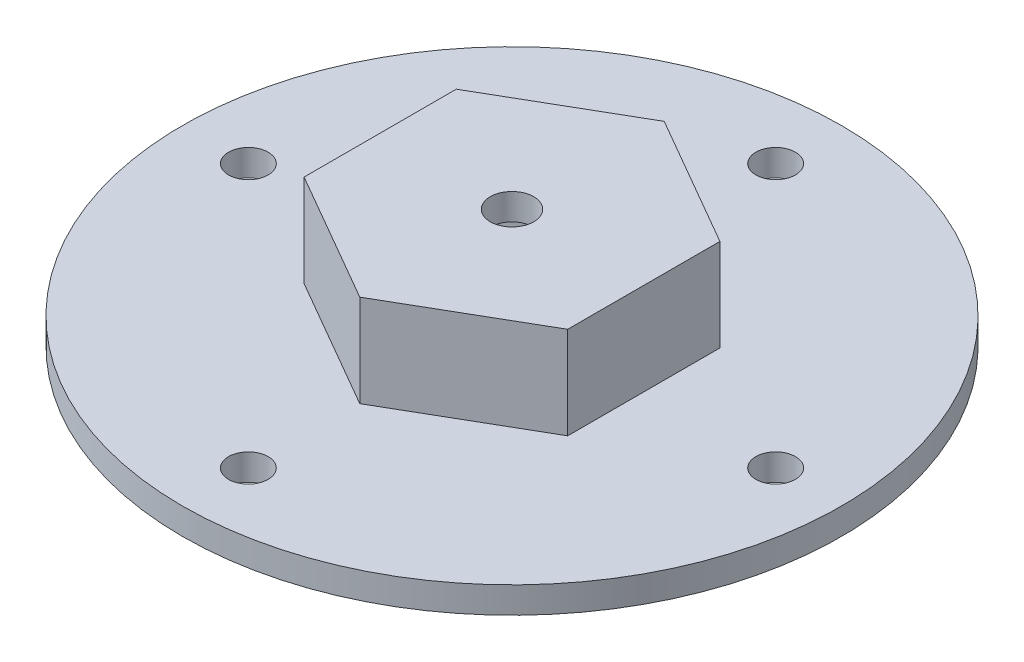
SolidWorks part; units mm, degrees
ref_plane "前视基准面" through (0, 0, 0) normal (0, 0, 1) x (1, 0, 0)
ref_plane "上视基准面" through (0, 0, 0) normal (0, 1, 0) x (1, 0, 0)
ref_plane "右视基准面" through (0, 0, 0) normal (1, 0, 0) x (0, 0, -1)
sketch "Sketch1" plane through (0, 0, 0) normal (0, 1, 0) x (1, 0, 0)
  circle A0 centre (0, 0) radius 25
  dimension "D1" = 50
extrude "Boss-Extrude1" add sketch "Sketch1" along normal blind 2
sketch "Sketch2" plane through (0, 2, 0) normal (0, 1, 0) x (1, 0, 0)
  circle A0 centre (0, 0) radius 20 construction
  circle A1 centre (0, 20) radius 1.5
  circle A2 centre (20, 0) radius 1.5
  circle A3 centre (0, -20) radius 1.5
  circle A4 centre (-20, 0) radius 1.5
  dimension "D1" = 4
extrude "Cut-Extrude1" cut sketch "Sketch2" against normal blind 3
sketch "Sketch3" plane through (0, 2, 0) normal (0, 1, 0) x (1, 0, 0)
  line L1 (0, 11.547) -> (-10, 5.7735)
  line L2 (-10, 5.7735) -> (-10, -5.7735)
  line L3 (-10, -5.7735) -> (0, -11.547)
  line L4 (0, -11.547) -> (10, -5.7735)
  line L5 (10, -5.7735) -> (10, 5.7735)
  line L6 (10, 5.7735) -> (0, 11.547)
  circle A0 centre (0, 0) radius 10 construction
extrude "Boss-Extrude2" add sketch "Sketch3" along normal blind 7
sketch "Sketch4" plane through (0, 0, 0) normal (0, -1, 0) x (1, 0, 0)
  line L1 (0, 5.7735) -> (-5, 2.8868)
  line L2 (-5, 2.8868) -> (-5, -2.8868)
  line L3 (-5, -2.8868) -> (0, -5.7735)
  line L4 (0, -5.7735) -> (5, -2.8868)
  line L5 (5, -2.8868) -> (5, 2.8868)
  line L6 (5, 2.8868) -> (0, 5.7735)
  circle A0 centre (0, 0) radius 5 construction
extrude "Cut-Extrude2" cut sketch "Sketch4" against normal blind 7
sketch "Sketch5" plane through (-10, 0, 0) normal (-1, 0, 0) x (0, 0, 1)
  line L0 (-5.7735, 2) -> (5.7735, 2) construction
  point P2 (0, 0)
  point P3 (0, 5)
  dimension "D1" = 3
hole_wizard "M4 Tapped Hole1" positions "Sketch6" profile "Sketch8" tap size "M4" standard "DIN"
sketch "Sketch6" plane through (-10, 0, 0) normal (-1, 0, 0) x (0, 0, 1)
  point P0 (0, 5)
sketch "Sketch8" plane through (-10, 5, 0) normal (0, 1, 0) x (0, 0, 1)
  line L0 (0, 0) -> (0, 5)
  line L1 (0, 5) -> (1.65, 5)
  line L2 (1.65, 5) -> (1.65, 0)
  line L5 (1.65, 0) -> (0, 0)
  line L11 (0, -6.35) -> (0, 107.95) construction
  dimension "Thru Tap Drill Dia." = 3.3
  dimension "Thru Tap Drill Depth" = 5
cosmetic thread "Hole Thread1" parameters "D2"=4
sketch "Sketch9" plane through (0, 9, 0) normal (0, 1, 0) x (1, 0, 0)
  point P0 (0, 0)
  point P1 (0, 0)
hole_wizard "M4 Tapped Hole2" positions "Sketch10" profile "Sketch11" tap size "M4" standard "DIN" end condition up to next
sketch "Sketch10" plane through (0, 9, 0) normal (0, 1, 0) x (1, 0, 0)
  point P0 (0, 0)
sketch "Sketch11" plane through (0, 9, 0) normal (1, 0, 0) x (0, 0, 1)
  line L0 (0, 0) -> (0, 2)
  line L1 (0, 2) -> (1.65, 2)
  line L2 (1.65, 2) -> (1.65, 0)
  line L5 (1.65, 0) -> (0, 0)
  line L11 (0, -6.35) -> (0, 107.95) construction
  dimension "Thru Tap Drill Dia." = 3.3
  dimension "Thru Tap Drill Depth" = 2
cosmetic thread "Hole Thread2" parameters "D2"=4
